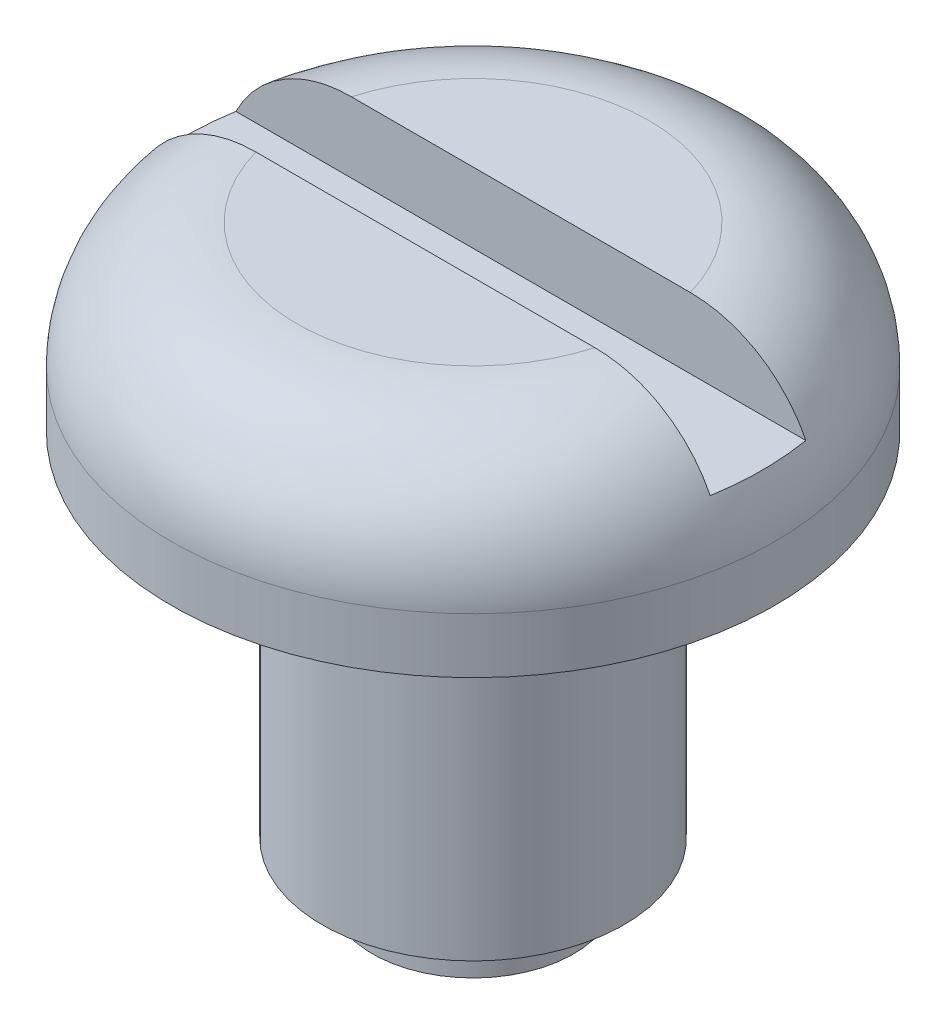
SolidWorks part; units mm, degrees
ref_plane "Front Plane" through (0, 0, 0) normal (0, 0, 1) x (1, 0, 0)
ref_plane "Top Plane" through (0, 0, 0) normal (0, 1, 0) x (1, 0, 0)
ref_plane "Right Plane" through (0, 0, 0) normal (1, 0, 0) x (0, 0, -1)
sketch "Sketch1" plane through (0, 0, 0) normal (0, 0, 1) x (1, 0, 0)
  line L0 (0, 0) -> (0, 11.6) construction
  line L1 (0, 0) -> (-2, 0)
  line L2 (-2, 0) -> (-2, 1)
  line L3 (-2, 1) -> (-3, 1)
  line L4 (-3, 1) -> (-3, 8)
  line L5 (-3, 8) -> (-6, 8)
  line L6 (-6, 8) -> (-6, 9.1)
  line L7 (-3.5, 11.6) -> (0, 11.6)
  line L8 (0, 0) -> (0, 11.6)
  arc A0 (-6, 9.1) -> (-3.5, 11.6) centre (-3.5, 9.1) cw
  dimension "D6" = 2.5
  dimension "D1" = 11.6
  dimension "D2" = 4
  dimension "D3" = 6
  dimension "D4" = 1
  dimension "D5" = 7
  dimension "D7" = 12
revolve "Revolve1" add sketch "Sketch1" angle 360 about L0
cosmetic thread "Cosmetic Thread1" parameters "D1"=7, "D2"=4.891
sketch "Sketch2" plane through (0, 0, 0) normal (1, 0, 0) x (0, 0, -1)
  line L0 (-0.95, 11.6) -> (-0.95, 10.2)
  line L1 (3.5, 11.6) -> (-3.5, 11.6) construction
  line L2 (-0.95, 10.2) -> (0.95, 10.2)
  line L3 (0.95, 10.2) -> (0.95, 11.6)
  line L4 (0.95, 11.6) -> (-0.95, 11.6)
  line L5 (0, 0) -> (0, 6.9507) construction
  dimension "D1" = 1.9
  dimension "D2" = 1.4
extrude "Cut-Extrude1" cut sketch "Sketch2" against normal through all both and the other way through all
